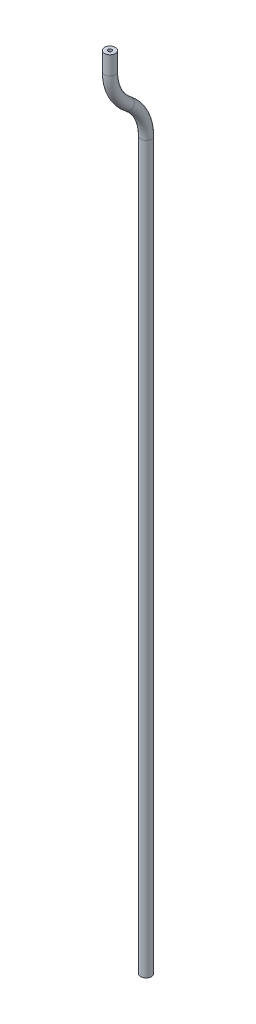
SolidWorks part; units mm, degrees
ref_plane "Front Plane" through (0, 0, 0) normal (0, 0, 1) x (1, 0, 0)
ref_plane "Top Plane" through (0, 0, 0) normal (0, 1, 0) x (1, 0, 0)
ref_plane "Right Plane" through (0, 0, 0) normal (1, 0, 0) x (0, 0, -1)
sketch "Illustrative smooth utility route" plane through (0, 0, 0) normal (1, 0, 0) x (0, 0, -1)
  line L0 (-16.25, 0) -> (-16.25, -6)
  line L1 (-4.5, -30) -> (-4.5, -266)
  arc A0 (-16.25, -6) -> (-10.375, -18) centre (-1.0572, -6) ccw
  arc A1 (-10.375, -18) -> (-4.5, -30) centre (-19.6928, -30) cw
sketch "Utility circular cross section" plane through (0, 0, 0) normal (0, 1, 0) x (1, 0, 0)
  circle A0 centre (0, -16.25) radius 1.75
  circle A1 centre (0, -16.25) radius 0.6
sweep "Native hollow utility sweep" add profiles "Utility circular cross section" path "Illustrative smooth utility route"
